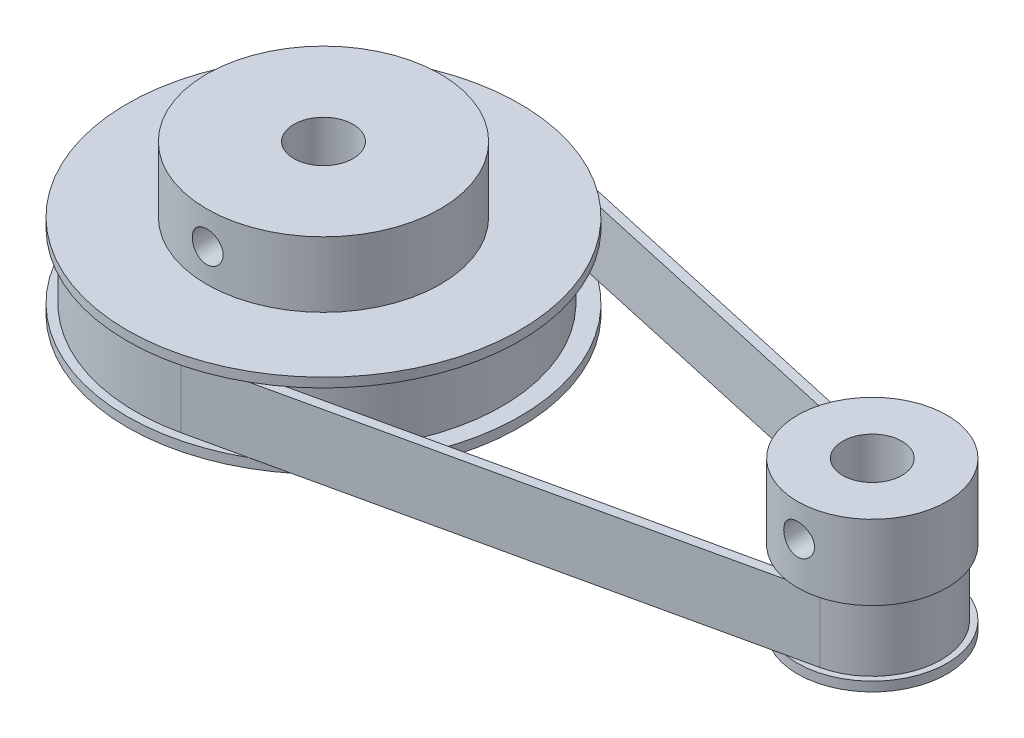
SolidWorks part; units mm, degrees
ref_plane "Front Plane" through (0, 0, 0) normal (0, 0, 1) x (1, 0, 0)
ref_plane "Top Plane" through (0, 0, 0) normal (0, 1, 0) x (1, 0, 0)
ref_plane "Right Plane" through (0, 0, 0) normal (1, 0, 0) x (0, 0, -1)
sketch "Sketch1" plane through (0, 0, 0) normal (0, 1, 0) x (1, 0, 0)
  line L0 (1.3802, -6.2136) -> (-54.5884, -18.6456)
  line L1 (-54.5884, 18.6456) -> (1.3802, 6.2136)
  circle A0 centre (0, 0) radius 6.365
  circle A1 centre (-58.73, 0) radius 19.1
  dimension "D1" = 38.2
  dimension "D2" = 12.73
  dimension "D3" = 58.73
sketch "Sketch2" plane through (0, 0, 0) normal (0, 1, 0) x (1, 0, 0)
  line L0 (-54.5884, 18.6456) -> (1.3802, 6.2136) construction
  line L1 (1.3802, -6.2136) -> (-54.5884, -18.6456) construction
  line L2 (-54.5884, 18.6456) -> (1.3802, 6.2136)
  line L3 (1.3802, -6.2136) -> (-54.5884, -18.6456)
  circle A0 centre (-58.73, 0) radius 19.1 construction
  circle A1 centre (0, 0) radius 6.365 construction
  arc A2 (-54.5884, 18.6456) -> (-54.5884, -18.6456) centre (-58.73, 0) ccw
  arc A3 (1.3802, -6.2136) -> (1.3802, 6.2136) centre (0, 0) ccw
extrude "Boss-Extrude1" add sketch "Sketch1" along normal blind 3.5 contours A1 | A0
sketch "Sketch3" plane through (0, 3.5, 0) normal (0, 1, 0) x (1, 0, 0)
  circle A0 centre (-58.73, 0) radius 21
  circle A1 centre (0, 0) radius 8
  circle A2 centre (-58.73, 0) radius 19.1 construction
  dimension "D1" = 16
  dimension "D2" = 42
extrude "Boss-Extrude2" add sketch "Sketch3" along normal blind 1
mirror "Mirror1" about plane through (0, 0, 0) normal (0, 1, 0) of bodies 103 104
sketch "Sketch4" plane through (0, 4.5, 0) normal (0, 1, 0) x (1, 0, 0)
  circle A0 centre (-58.73, 0) radius 12.5
  circle A1 centre (0, 0) radius 8 construction
  circle A2 centre (0, 0) radius 8
  dimension "D1" = 25
extrude "Boss-Extrude3" add sketch "Sketch4" along normal blind 7
sketch "Sketch5" plane through (0, 11.5, 0) normal (0, 1, 0) x (1, 0, 0)
  circle A0 centre (0, 0) radius 3.175
  circle A1 centre (-58.73, 0) radius 3.175
  circle A4 centre (-58.73, 0) radius 12.5 construction
  dimension "D1" = 6.35
extrude "Cut-Extrude1" cut sketch "Sketch5" against normal through all
ref_plane "Plane1" through (0, 0, 12.5) normal (0, 0, 1) x (1, 0, 0)
ref_plane "Plane2" through (0, 0, 8) normal (0, 0, 1) x (1, 0, 0)
sketch "Sketch6" plane through (0, 0, 12.5) normal (0, 0, 1) x (1, 0, 0)
  line L0 (-55.555, 11.5) -> (-61.905, 11.5) construction
  line L1 (-55.555, 11.5) -> (-61.905, 11.5)
  point P2 (-58.73, 8)
  point P3 (-58.73, 11.5)
  point P4 (-58.73, 8)
  dimension "D1" = 3.5
hole_wizard "M4x0.7 Tapped Hole1" positions "Sketch6" profile "Sketch8" tap size "M4x0.7" standard "ANSI Metric"
sketch "Sketch8" plane through (-58.73, 8, 12.5) normal (1, 0, 0) x (0, -1, 0)
  line L0 (0, 0) -> (0, 16.6674)
  line L1 (0, 16.6674) -> (1.65, 15.676)
  line L2 (1.65, 15.676) -> (1.65, 0)
  line L5 (1.65, 0) -> (0, 0)
  line L10 (0, 16.6674) -> (-1.65, 15.676) construction
  line L11 (0, -6.35) -> (0, 107.95) construction
  dimension "Tap Drill Dia." = 3.3
  dimension "Tap Drill Depth" = 15.676
  dimension "Drill Angle" = 118
cosmetic thread "Hole Thread1" parameters "D1"=8, "D2"=4
cosmetic thread "Hole Thread2" parameters "D1"=8, "D2"=4
sketch "Sketch9" plane through (0, 0, 8) normal (0, 0, 1) x (1, 0, 0)
  line L0 (-6.365, 3.5) -> (6.365, 3.5) construction
  point P0 (0, 8)
  dimension "D1" = 4.5
hole_wizard "M4x0.7 Tapped Hole2" positions "Sketch9" profile "Sketch10" tap size "M4x0.7" standard "ANSI Metric"
sketch "Sketch10" plane through (0, 8, 8) normal (1, 0, 0) x (0, -1, 0)
  line L0 (0, 0) -> (0, 12.1664)
  line L1 (0, 12.1664) -> (1.65, 11.175)
  line L2 (1.65, 11.175) -> (1.65, 0)
  line L5 (1.65, 0) -> (0, 0)
  line L10 (0, 12.1664) -> (-1.65, 11.175) construction
  line L11 (0, -6.35) -> (0, 107.95) construction
  dimension "Tap Drill Dia." = 3.3
  dimension "Tap Drill Depth" = 11.175
  dimension "Drill Angle" = 118
cosmetic thread "Hole Thread3" parameters "D1"=8, "D2"=4
extrude "Extrude-Thin1" add sketch "Sketch2" along normal mid plane 7 separate body thin thin type one direction wall 1
